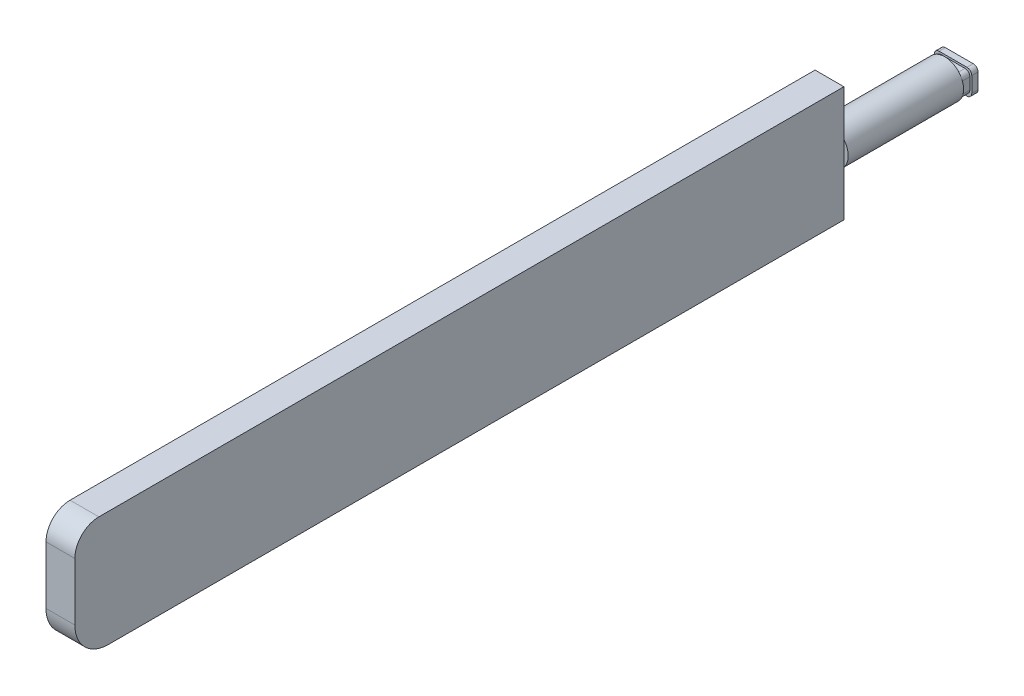
SolidWorks part; units mm, degrees
material "6061 Alloy"
ref_plane "Front Plane" through (0, 0, 0) normal (0, 0, 1) x (1, 0, 0)
ref_plane "Top Plane" through (0, 0, 0) normal (0, 1, 0) x (1, 0, 0)
ref_plane "Right Plane" through (0, 0, 0) normal (1, 0, 0) x (0, 0, -1)
sketch "Sketch1" plane through (0, 0, 0) normal (0, 0, 1) x (1, 0, 0)
  line L1 (-19.5, 13) -> (19.5, 13)
  line L2 (-19.5, 13) -> (-19.5, -13)
  line L3 (-19.5, -13) -> (19.5, -13)
  line L4 (19.5, 13) -> (19.5, -13)
  line L5 (0, -13) -> (0, 13) construction
  line L6 (-19.5, 0) -> (19.5, 0) construction
  point P0 (0, 0)
  dimension "D1" = 39
  dimension "D2" = 26
extrude "Boss-Extrude1" add sketch "Sketch1" along normal blind 15
sketch "Sketch2" plane through (0, 0, 15) normal (0, 0, 1) x (1, 0, 0)
  line L0 (17.5, 11) -> (-17.5, 11)
  line L1 (-17.5, 11) -> (-17.5, -11)
  line L2 (-17.5, -11) -> (17.5, -11)
  line L3 (17.5, -11) -> (17.5, 11)
  line L8 (19.5, -13) -> (19.5, 13)
  line L9 (19.5, 13) -> (-19.5, 13)
  line L10 (-19.5, 13) -> (-19.5, -13)
  line L11 (-19.5, -13) -> (19.5, -13)
  line L12 (19.5, -13) -> (19.5, 13)
  line L13 (19.5, 13) -> (-19.5, 13)
  line L14 (-19.5, 13) -> (-19.5, -13)
  line L15 (-19.5, -13) -> (19.5, -13)
  line M9 (19.5, -13) -> (19.5, 13)
  line M10 (19.5, 13) -> (-19.5, 13)
  line M11 (-19.5, 13) -> (-19.5, -13)
  line M12 (-19.5, -13) -> (19.5, -13)
  dimension "D1" = 0
  dimension "D2" = 2
extrude "Cut-Extrude1" cut sketch "Sketch2" against normal blind 8.5 contours L3 L2 L1 L0 M12 M9 M10 M11
fillet "Fillet1" radius 5 8 edges at (19.5, -13, 3.25) (19.5, 13, 3.25) (-19.5, -13, 3.25) (-19.5, 13, 3.25) (-17.5, -11, 10.75) (17.5, -11, 10.75) (17.5, 11, 10.75) (-17.5, 11, 10.75)
sketch "Sketch3" plane through (0, 0, 15) normal (0, 0, 1) x (1, 0, 0)
  circle A0 centre (0, 0) radius 19.5
  dimension "D1" = 39
extrude "Boss-Extrude2" add sketch "Sketch3" along normal blind 120
sketch "Sketch4" plane through (0, 0, 0) normal (1, 0, 0) x (0, 0, -1)
  line L0 (-135, 19.5) -> (-135, -19.5) construction
  line L1 (-135, 19.5) -> (-135, -19.5)
  line L2 (-135, 60) -> (-135, 19.5)
  line L3 (-135, -19.5) -> (-135, -60)
  line L4 (-135, 60) -> (-935, 60)
  line L5 (-935, 60) -> (-935, -60)
  line L6 (-935, -60) -> (-135, -60)
  dimension "D1" = 120
  dimension "D2" = 800
extrude "Boss-Extrude3" add sketch "Sketch4" along normal mid plane 30
fillet "Fillet2" radius 25 1 edges at (0, 60, 935)
fillet "Fillet3" radius 35 1 edges at (0, -60, 935)
